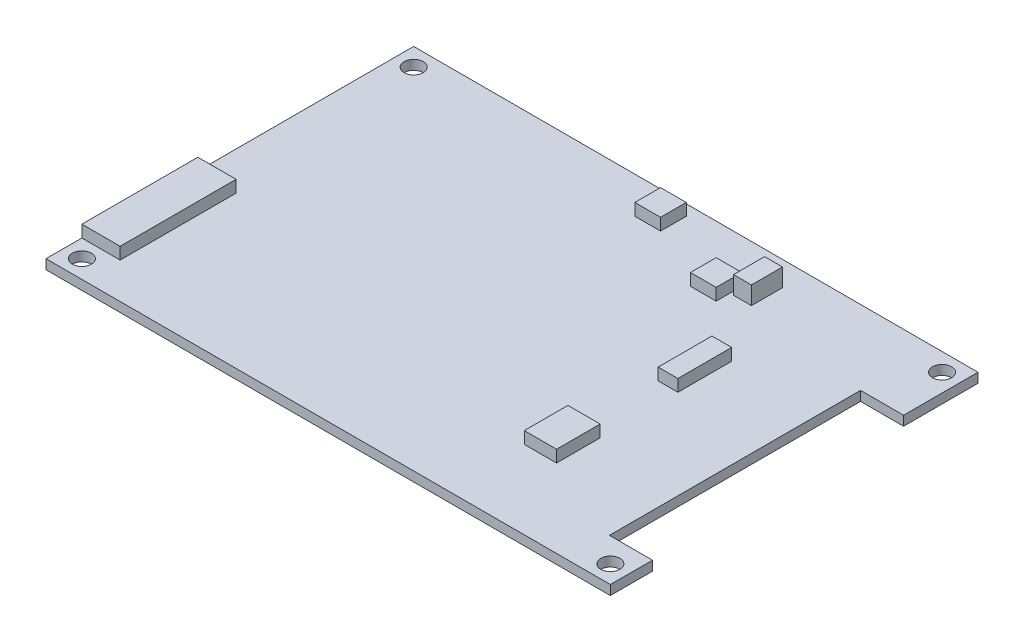
SolidWorks part; units mm, degrees
ref_plane "前视基准面" through (0, 0, 0) normal (0, 0, 1) x (1, 0, 0)
ref_plane "上视基准面" through (0, 0, 0) normal (0, 1, 0) x (1, 0, 0)
ref_plane "右视基准面" through (0, 0, 0) normal (1, 0, 0) x (0, 0, -1)
sketch "草图1" plane through (0, 0, 0) normal (0, 1, 0) x (1, 0, 0)
  line L1 (0, 0) -> (94.4, 0)
  line L2 (0, 0) -> (0, -61.5)
  line L3 (0, -61.5) -> (94.4, -61.5)
  line L4 (94.4, 0) -> (94.4, -61.5)
  line L5 (94.4, -12.45) -> (87.2, -12.45)
  line L6 (94.4, -12.45) -> (94.4, -54.45)
  line L7 (94.4, -54.45) -> (87.2, -54.45)
  line L8 (87.2, -12.45) -> (87.2, -54.45)
  line L9 (3, -3) -> (91.4, -3) construction
  line L10 (3, -3) -> (3, -58.5) construction
  line L11 (3, -58.5) -> (91.4, -58.5) construction
  line L12 (91.4, -3) -> (91.4, -58.5) construction
  circle A0 centre (3, -3) radius 1.6
  circle A1 centre (3, -58.5) radius 1.6
  circle A2 centre (91.4, -3) radius 1.6
  circle A3 centre (91.4, -58.5) radius 1.6
  dimension "D10" = 3.2
  dimension "D11" = 3.2
  dimension "D12" = 3.2
  dimension "D13" = 3.2
  dimension "D1" = 94.4
  dimension "D2" = 61.5
  dimension "D3" = 7.2
  dimension "D4" = 42
  dimension "D5" = 12.45
  dimension "D6" = 3
  dimension "D7" = 3
  dimension "D8" = 3
  dimension "D9" = 3
extrude "凸台-拉伸1" add sketch "草图1" along normal blind 1.6 contours L8 L5 L4 L1 L2 L3 L7
sketch "草图2" plane through (0, 1.6, 0) normal (0, 1, 0) x (1, 0, 0)
  line L0 (0, 0) -> (0, -61.5) construction
  line L1 (0, -55.5) -> (6.4, -55.5)
  line L2 (0, -55.5) -> (0, -36.1)
  line L3 (0, -36.1) -> (6.4, -36.1)
  line L4 (6.4, -55.5) -> (6.4, -36.1)
  line L5 (0, -61.5) -> (94.4, -61.5) construction
  line L6 (66.9, -41.1) -> (72.3, -41.1)
  line L7 (66.9, -41.1) -> (66.9, -48.4)
  line L8 (66.9, -48.4) -> (72.3, -48.4)
  line L9 (72.3, -41.1) -> (72.3, -48.4)
  line L10 (68.9, -19) -> (72.2, -19)
  line L11 (68.9, -19) -> (68.9, -28)
  line L12 (68.9, -28) -> (72.2, -28)
  line L13 (72.2, -19) -> (72.2, -28)
  line L14 (0, 0) -> (94.4, 0) construction
  line L15 (43.1, -1.8) -> (47.4, -1.8)
  line L16 (43.1, -1.8) -> (43.1, -6.1)
  line L17 (43.1, -6.1) -> (47.4, -6.1)
  line L18 (47.4, -1.8) -> (47.4, -6.1)
  line L19 (57.9, -7.3) -> (62.2, -7.3)
  line L20 (57.9, -7.3) -> (57.9, -11.6)
  line L21 (57.9, -11.6) -> (62.2, -11.6)
  line L22 (62.2, -7.3) -> (62.2, -11.6)
  dimension "D1" = 6
  dimension "D2" = 6.4
  dimension "D3" = 19.4
  dimension "D4" = 13.1
  dimension "D5" = 66.9
  dimension "D6" = 5.4
  dimension "D7" = 7.3
  dimension "D8" = 33.5
  dimension "D9" = 68.9
  dimension "D10" = 3.3
  dimension "D11" = 9
  dimension "D12" = 43.1
  dimension "D13" = 1.8
  dimension "D14" = 4.3
  dimension "D15" = 4.3
  dimension "D16" = 4.3
  dimension "D17" = 4.3
  dimension "D18" = 57.9
  dimension "D19" = 7.3
extrude "凸台-拉伸2" add sketch "草图2" along normal blind 2
sketch "草图3" plane through (0, 1.6, 0) normal (0, 1, 0) x (1, 0, 0)
  line L0 (0, 0) -> (0, -36.1) construction
  line L1 (62.8, -4.1) -> (65.8, -4.1)
  line L2 (62.8, -4.1) -> (62.8, -9.3)
  line L3 (62.8, -9.3) -> (65.8, -9.3)
  line L4 (65.8, -4.1) -> (65.8, -9.3)
  line L5 (0, 0) -> (94.4, 0) construction
  dimension "D1" = 62.8
  dimension "D2" = 4.1
  dimension "D3" = 3
  dimension "D4" = 5.2
extrude "凸台-拉伸3" add sketch "草图3" along normal blind 3
